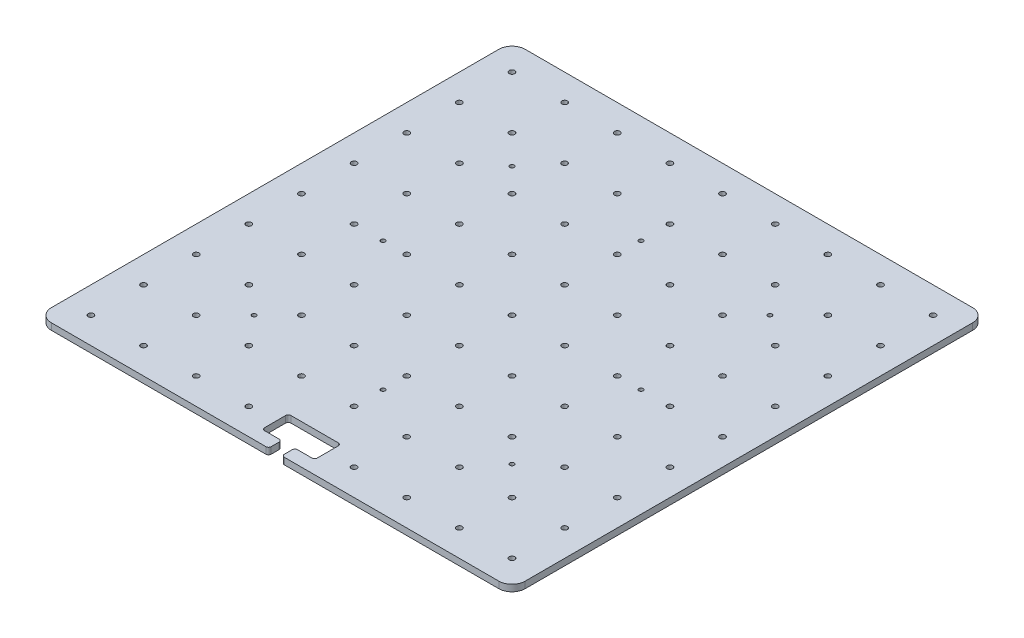
SolidWorks part; units mm, degrees
ref_plane "前视基准面" through (0, 0, 0) normal (0, 0, 1) x (1, 0, 0)
ref_plane "上视基准面" through (0, 0, 0) normal (0, 1, 0) x (1, 0, 0)
ref_plane "右视基准面" through (0, 0, 0) normal (1, 0, 0) x (0, 0, -1)
sketch "草图1" plane through (0, 0, 0) normal (0, 1, 0) x (1, 0, 0)
  line L1 (-180, 180) -> (180, 180)
  line L2 (-180, 180) -> (-180, -180)
  line L3 (-180, -180) -> (180, -180)
  line L4 (180, 180) -> (180, -180)
  line L5 (-180, 180) -> (180, -180) construction
  line L6 (-180, -180) -> (180, 180) construction
  point P0 (0, 0)
  dimension "D1" = 360
  dimension "D2" = 360
extrude "凸台-拉伸1" add sketch "草图1" along normal blind 5
sketch "草图2" plane through (0, 5, 0) normal (0, 1, 0) x (1, 0, 0)
  line L0 (-261.6955, 0) -> (310.1755, 0) construction
  line L1 (0, 354.8743) -> (0, -385.5595) construction
  line L2 (0, 0) -> (40, 0) construction
  line L3 (0, 0) -> (0, 40) construction
  circle A0 centre (0, 0) radius 2.1
  circle A1 centre (40, 0) radius 2.1
  circle A2 centre (80, 0) radius 2.1
  circle A3 centre (120, 0) radius 2.1
  circle A4 centre (160, 0) radius 2.1
  circle A5 centre (40, 40) radius 2.1
  circle A6 centre (80, 40) radius 2.1
  circle A7 centre (120, 40) radius 2.1
  circle A8 centre (160, 40) radius 2.1
  circle A9 centre (40, 80) radius 2.1
  circle A10 centre (80, 80) radius 2.1
  circle A11 centre (120, 80) radius 2.1
  circle A12 centre (160, 80) radius 2.1
  circle A13 centre (40, 120) radius 2.1
  circle A14 centre (80, 120) radius 2.1
  circle A15 centre (120, 120) radius 2.1
  circle A16 centre (160, 120) radius 2.1
  circle A17 centre (40, 160) radius 2.1
  circle A18 centre (80, 160) radius 2.1
  circle A19 centre (120, 160) radius 2.1
  circle A20 centre (160, 160) radius 2.1
  circle A21 centre (0, 40) radius 2.1
  circle A22 centre (0, 80) radius 2.1
  circle A23 centre (0, 120) radius 2.1
  circle A24 centre (0, 160) radius 2.1
  circle A25 centre (0, -160) radius 2.1
  circle A26 centre (0, -120) radius 2.1
  circle A27 centre (0, -80) radius 2.1
  circle A28 centre (0, -40) radius 2.1
  circle A29 centre (160, -160) radius 2.1
  circle A30 centre (120, -160) radius 2.1
  circle A31 centre (80, -160) radius 2.1
  circle A32 centre (40, -160) radius 2.1
  circle A33 centre (160, -120) radius 2.1
  circle A34 centre (120, -120) radius 2.1
  circle A35 centre (80, -120) radius 2.1
  circle A36 centre (40, -120) radius 2.1
  circle A37 centre (160, -80) radius 2.1
  circle A38 centre (120, -80) radius 2.1
  circle A39 centre (80, -80) radius 2.1
  circle A40 centre (40, -80) radius 2.1
  circle A41 centre (160, -40) radius 2.1
  circle A42 centre (120, -40) radius 2.1
  circle A43 centre (80, -40) radius 2.1
  circle A44 centre (40, -40) radius 2.1
  circle A45 centre (-40, -40) radius 2.1
  circle A46 centre (-80, -40) radius 2.1
  circle A47 centre (-120, -40) radius 2.1
  circle A48 centre (-160, -40) radius 2.1
  circle A49 centre (-40, -80) radius 2.1
  circle A50 centre (-80, -80) radius 2.1
  circle A51 centre (-120, -80) radius 2.1
  circle A52 centre (-160, -80) radius 2.1
  circle A53 centre (-40, -120) radius 2.1
  circle A54 centre (-80, -120) radius 2.1
  circle A55 centre (-120, -120) radius 2.1
  circle A56 centre (-160, -120) radius 2.1
  circle A57 centre (-40, -160) radius 2.1
  circle A58 centre (-80, -160) radius 2.1
  circle A59 centre (-120, -160) radius 2.1
  circle A60 centre (-160, -160) radius 2.1
  circle A61 centre (-160, 160) radius 2.1
  circle A62 centre (-120, 160) radius 2.1
  circle A63 centre (-80, 160) radius 2.1
  circle A64 centre (-40, 160) radius 2.1
  circle A65 centre (-160, 120) radius 2.1
  circle A66 centre (-120, 120) radius 2.1
  circle A67 centre (-80, 120) radius 2.1
  circle A68 centre (-40, 120) radius 2.1
  circle A69 centre (-160, 80) radius 2.1
  circle A70 centre (-120, 80) radius 2.1
  circle A71 centre (-80, 80) radius 2.1
  circle A72 centre (-40, 80) radius 2.1
  circle A73 centre (-160, 40) radius 2.1
  circle A74 centre (-120, 40) radius 2.1
  circle A75 centre (-80, 40) radius 2.1
  circle A76 centre (-40, 40) radius 2.1
  circle A77 centre (-160, 0) radius 2.1
  circle A78 centre (-120, 0) radius 2.1
  circle A79 centre (-80, 0) radius 2.1
  circle A80 centre (-40, 0) radius 2.1
  dimension "D1" = 4.2
  dimension "D2" = 5
  dimension "D3" = 5
  dimension "D6" = 40
  dimension "D4" = 90
  dimension "D5" = 40
extrude "切除-拉伸1" cut sketch "草图2" against normal through all
fillet "圆角1" radius 10 4 edges at (-180, 2.5, 180) (180, 2.5, 180) (180, 2.5, -180) (-180, 2.5, -180)
sketch "草图3" plane through (0, 5, 0) normal (0, 1, 0) x (1, 0, 0)
  line L0 (0, 61.9578) -> (0, -237.0906) construction
  line L1 (5, -180) -> (5, -170)
  line L2 (-170, -180) -> (170, -180) construction
  line L3 (5, -170) -> (20, -170)
  line L4 (20, -170) -> (20, -150)
  line L5 (20, -150) -> (-20, -150)
  line L6 (5, -180) -> (-5, -180)
  line L7 (-20, -170) -> (-20, -150)
  line L8 (-5, -170) -> (-20, -170)
  line L9 (-5, -180) -> (-5, -170)
  line L10 (-358.7553, 0) -> (346.9152, 0) construction
  point P12 (0, -180)
  point P13 (0, -150)
  dimension "D1" = 10
  dimension "D2" = 20
  dimension "D3" = 5
  dimension "D4" = 20
extrude "切除-拉伸2" cut sketch "草图3" against normal through all
sketch "草图4" plane through (0, 5, 0) normal (0, 1, 0) x (1, 0, 0)
  line L0 (-333.9146, 0) -> (418.7222, 0) construction
  line L1 (0, 255.123) -> (0, -281.0545) construction
  line L7 (-98, 98) -> (98, -98) construction
  line L8 (-98, -98) -> (98, 98) construction
  circle A0 centre (98, 98) radius 1.6
  circle A1 centre (98, -98) radius 1.6
  circle A2 centre (-98, -98) radius 1.6
  circle A3 centre (-98, 98) radius 1.6
  circle A4 centre (98, 0) radius 1.6
  circle A5 centre (-98, 0) radius 1.6
  circle A6 centre (0, 98) radius 1.6
  circle A7 centre (0, -98) radius 1.6
  point P5 (0, 0)
  dimension "D3" = 3.2
  dimension "D4" = 3.2
  dimension "D5" = 196
  dimension "D6" = 3.2
  dimension "D7" = 196
  dimension "D1" = 196
  dimension "D2" = 196
extrude "切除-拉伸3" cut sketch "草图4" against normal blind 10
fillet "圆角2" radius 2 8 edges at (20, 2.5, 170) (20, 2.5, 150) (-20, 2.5, 150) (-20, 2.5, 170) (-5, 2.5, 170) (-5, 2.5, 180) (5, 2.5, 180) (5, 2.5, 170)
sketch3d "URDF Reference"
  line L0 (0, 0, 0) -> (10, 0, 0) construction
  line L1 (0, 0, 0) -> (0, 0, -10) construction
  point P0 (0, 0, 0)
